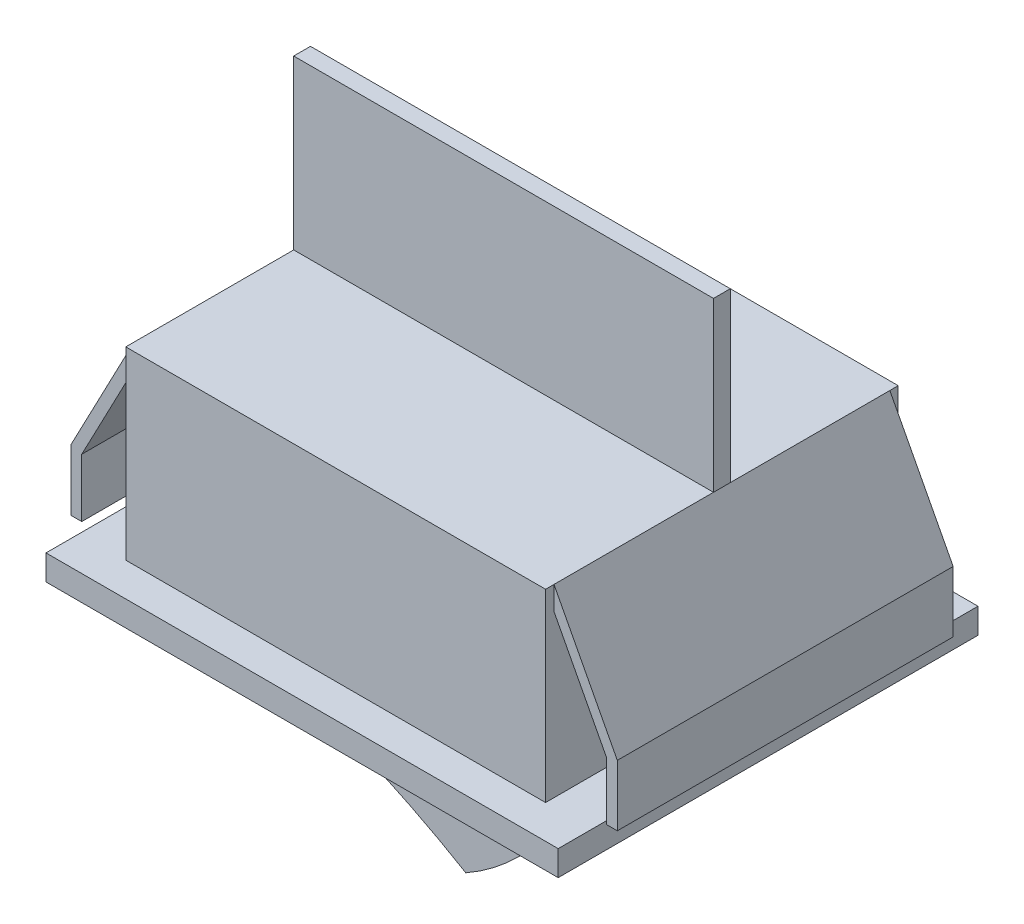
SolidWorks part; units mm, degrees
ref_plane "Front Plane" through (0, 0, 0) normal (0, 0, 1) x (1, 0, 0)
ref_plane "Top Plane" through (0, 0, 0) normal (0, 1, 0) x (1, 0, 0)
ref_plane "Right Plane" through (0, 0, 0) normal (1, 0, 0) x (0, 0, -1)
sketch "Sketch1" plane through (0, 0, 0) normal (0, 1, 0) x (1, 0, 0)
  line L1 (12.5, 10.5) -> (-12.5, 10.5)
  line L2 (12.5, 10.5) -> (12.5, -10.5)
  line L3 (12.5, -10.5) -> (-12.5, -10.5)
  line L4 (-12.5, 10.5) -> (-12.5, -10.5)
  line L5 (12.5, 10.5) -> (-12.5, -10.5) construction
  line L6 (12.5, -10.5) -> (-12.5, 10.5) construction
  point P0 (0, 0)
  dimension "D1" = 21
  dimension "D2" = 25
extrude "Boss-Extrude1" add sketch "Sketch1" along normal blind 11
sketch "Sketch2" plane through (0, 11, 0) normal (0, 1, 0) x (1, 0, 0)
  line L0 (-12.5, 10.5) -> (-12.5, -10.5) construction
  line L1 (12.5, 0.5) -> (-12.5, 0.5)
  line L2 (12.5, 0.5) -> (12.5, -0.5)
  line L3 (12.5, -0.5) -> (-12.5, -0.5)
  line L4 (-12.5, 0.5) -> (-12.5, -0.5)
  line L5 (12.5, 0.5) -> (-12.5, -0.5) construction
  line L6 (12.5, -0.5) -> (-12.5, 0.5) construction
  point P0 (0, 0)
  dimension "D1" = 1
extrude "Boss-Extrude2" add sketch "Sketch2" along normal blind 10
sketch "Sketch3" plane through (0, 0, 0) normal (0, 0, 1) x (1, 0, 0)
  line L0 (-12.5, 11) -> (-16.2714, 3.8115)
  line L1 (-16.2714, 3.8115) -> (-16.2714, 0.1787)
  line L2 (-16.2714, 0.1787) -> (-15.6214, 0.1787)
  line L3 (-15.6214, 0.1787) -> (-15.6214, 3.6514)
  line L4 (-15.6214, 3.6514) -> (-12.5, 9.6009)
  line L5 (-12.5, 11) -> (-12.5, 0) construction
  line L6 (-12.5, 9.6009) -> (-12.5, 11)
  dimension "D1" = 0.65
  dimension "D2" = 0.65
extrude "Boss-Extrude3" add sketch "Sketch3" along normal blind 10 and the other way blind 10
mirror "Mirror1" about plane through (0, 0, 0) normal (1, 0, 0) of "Boss-Extrude3"
sketch "Sketch4" plane through (0, 0, 0) normal (0, -1, 0) x (1, 0, 0)
  line L1 (15.25, 12.5) -> (-15.25, 12.5)
  line L2 (15.25, 12.5) -> (15.25, -12.5)
  line L3 (15.25, -12.5) -> (-15.25, -12.5)
  line L4 (-15.25, 12.5) -> (-15.25, -12.5)
  line L5 (15.25, 12.5) -> (-15.25, -12.5) construction
  line L6 (15.25, -12.5) -> (-15.25, 12.5) construction
  point P0 (0, 0)
  dimension "D1" = 30.5
  dimension "D2" = 25
extrude "Boss-Extrude4" add sketch "Sketch4" along normal blind 1.5
sketch "Sketch5" plane through (0, 0, 0) normal (0, 0, 1) x (1, 0, 0)
  line L0 (11.75, -1.5) -> (-11.75, -1.5)
  line L1 (-15.25, -1.5) -> (15.25, -1.5) construction
  line L2 (0, 0) -> (0, -1.5) construction
  line L3 (-11.75, -1.5) -> (5.75, -1.5)
  line L4 (5.75, -1.5) -> (5.75, -8) construction
  arc A0 (5.75, -8) -> (-11.75, -1.5) centre (-20.9025, -52.9489) ccw
  arc A1 (5.75, -8) -> (11.75, -1.5) centre (-1.4652, 4.6794) ccw
  arc A2 (11.75, -1.5) -> (-14.8859, -1.0398) centre (-1.4652, 4.6794) ccw construction
  arc A3 (-14.8859, -1.0398) -> (5.75, -8) centre (-1.4652, 4.6794) ccw construction
  arc A4 (-14.8859, -1.0398) -> (5.75, -8) centre (-20.9025, -52.9489) ccw construction
  arc A5 (-11.75, -1.5) -> (-14.8859, -1.0398) centre (-20.9025, -52.9489) ccw construction
  point P5 (0, -1.5)
  dimension "D1" = 23.5
  dimension "D2" = 17.5
  dimension "D3" = 6.5
extrude "Boss-Extrude5" add sketch "Sketch5" along normal blind 8.5 and the other way blind 8.5 contours L0 A1 A0
